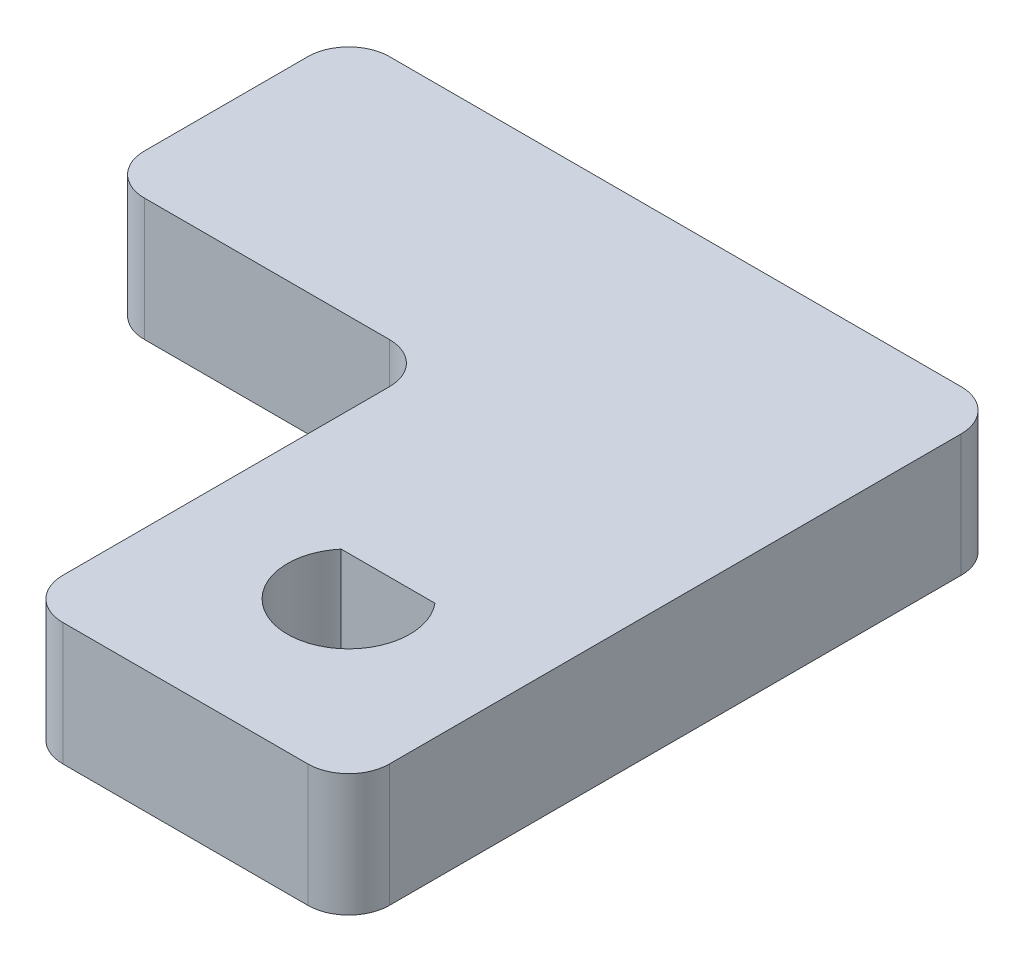
SolidWorks part; units mm, degrees
ref_plane "Front Plane" through (0, 0, 0) normal (0, 0, 1) x (1, 0, 0)
ref_plane "Top Plane" through (0, 0, 0) normal (0, 1, 0) x (1, 0, 0)
ref_plane "Right Plane" through (0, 0, 0) normal (1, 0, 0) x (0, 0, -1)
sketch "Sketch1" plane through (0, 0, 0) normal (0, 1, 0) x (1, 0, 0)
  line L1 (-6.2347, -2) -> (-14.2347, -2)
  line L2 (-6.2347, -2) -> (-6.2347, 8)
  line L4 (-14.2347, -2) -> (-14.2347, 8)
  line L7 (-14.2347, 8) -> (-22.2347, 8)
  line L8 (-6.2347, 8) -> (-6.2347, 14)
  line L9 (-6.2347, 14) -> (-22.2347, 14)
  line L10 (-22.2347, 8) -> (-22.2347, 14)
  point P0 (0, 0)
  dimension "D1" = 8
  dimension "D2" = 10
  dimension "D3" = 16
  dimension "D4" = 6
extrude "Boss-Extrude2" add sketch "Sketch1" along normal blind 3
fillet "Fillet1" radius 1 1 edges at (-22.2347, 1.5, -14)
fillet "Fillet2" radius 1 1 edges at (-22.2347, 1.5, -8)
fillet "Fillet3" radius 1 1 edges at (-6.2347, 1.5, -14)
fillet "Fillet4" radius 1 1 edges at (-14.2347, 1.5, 2)
fillet "Fillet5" radius 1 1 edges at (-6.2347, 1.5, 2)
fillet "Fillet6" radius 1 1 edges at (-14.2347, 1.5, -8)
sketch "Sketch3" plane through (0, 3, 0) normal (0, 1, 0) x (1, 0, 0)
  line L0 (-6.2347, -1) -> (-6.2347, 13) construction
  line L1 (-13.2347, -2) -> (-7.2347, -2) construction
  line L5 (-11.3832, 2.9648) -> (-9.0862, 2.9648)
  arc A0 (-11.3832, 2.9648) -> (-9.0862, 2.9648) centre (-10.2347, 2) ccw
  point P4 (-10.2347, -2)
  point P7 (-10.2347, 3.5)
  dimension "D1" = 3
  dimension "D2" = 4
  dimension "D3" = 4
extrude "Cut-Extrude2" cut sketch "Sketch3" against normal blind 3
